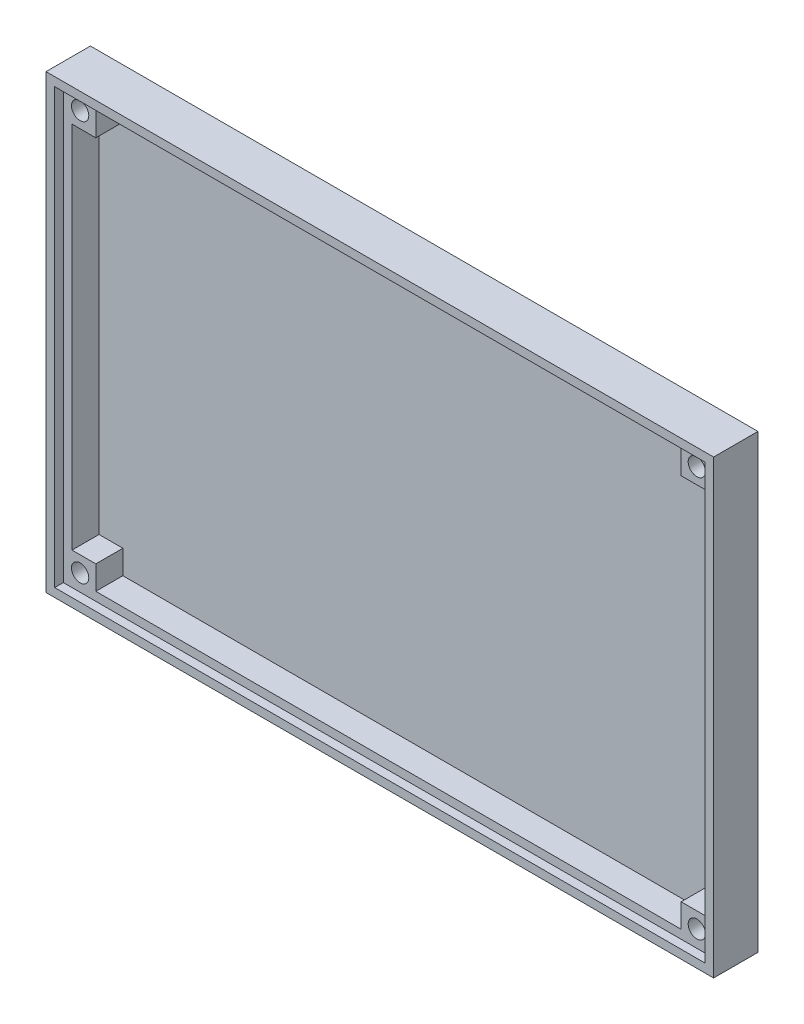
SolidWorks part; units mm, degrees
ref_plane "Front Plane" through (0, 0, 0) normal (0, 0, 1) x (1, 0, 0)
ref_plane "Top Plane" through (0, 0, 0) normal (0, 1, 0) x (1, 0, 0)
ref_plane "Right Plane" through (0, 0, 0) normal (1, 0, 0) x (0, 0, -1)
sketch "Sketch1" plane through (0, 0, 0) normal (0, 0, 1) x (1, 0, 0)
  line L1 (-60.1, 40.1) -> (60.1, 40.1)
  line L2 (-60.1, 40.1) -> (-60.1, -40.1)
  line L3 (-60.1, -40.1) -> (60.1, -40.1)
  line L4 (60.1, 40.1) -> (60.1, -40.1)
  line L5 (-60.1, 40.1) -> (60.1, -40.1) construction
  line L6 (-60.1, -40.1) -> (60.1, 40.1) construction
  point P0 (0, 0)
  dimension "D1" = 80.2
  dimension "D2" = 120.2
extrude "Boss-Extrude1" add sketch "Sketch1" along normal blind 1.6
sketch "Sketch2" plane through (0, 0, 0) normal (0, 0, 1) x (1, 0, 0)
  line L0 (-60.1, 40.1) -> (-60.1, -40.1)
  line L1 (-60.1, -40.1) -> (60.1, -40.1)
  line L2 (60.1, -40.1) -> (60.1, 40.1)
  line L3 (60.1, 40.1) -> (-60.1, 40.1)
  line L4 (-61.7, 41.7) -> (-61.7, -41.7)
  line L5 (-61.7, -41.7) -> (61.7, -41.7)
  line L6 (61.7, -41.7) -> (61.7, 41.7)
  line L7 (61.7, 41.7) -> (-61.7, 41.7)
  dimension "D1" = 1.6
  dimension "D2" = 1.6
  dimension "D3" = 1.6
  dimension "D4" = 1.6
extrude "Boss-Extrude2" add sketch "Sketch2" along normal blind 8.2
sketch "Sketch3" plane through (0, 0, 1.6) normal (0, 0, 1) x (1, 0, 0)
  line L0 (60.1, -40.1) -> (60.1, 40.1) construction
  line L3 (-58.5, 34.1) -> (-54.1, 34.1)
  line L4 (-54.1, 38.5) -> (-54.1, 34.1)
  line L6 (60.1, 40.1) -> (60.1, -40.1)
  line L7 (58.5, 34.1) -> (54.1, 34.1)
  line L8 (54.1, 38.5) -> (54.1, 34.1)
  line L9 (60.1, -40.1) -> (60.1, 40.1) construction
  line L10 (60.1, 40.1) -> (-60.1, 40.1)
  line L11 (60.1, -40.1) -> (-60.1, -40.1)
  line L13 (58.5, -34.1) -> (54.1, -34.1)
  line L14 (54.1, -38.5) -> (54.1, -34.1)
  line L16 (-60.1, -40.1) -> (-60.1, 40.1)
  line L17 (-58.5, -34.1) -> (-54.1, -34.1)
  line L18 (-54.1, -38.5) -> (-54.1, -34.1)
  line L19 (54.1, 38.5) -> (-54.1, 38.5)
  line L20 (58.5, 34.1) -> (58.5, -34.1)
  line L21 (54.1, -38.5) -> (-54.1, -38.5)
  line L22 (-58.5, -34.1) -> (-58.5, 34.1)
  line L23 (-60.1, -40.1) -> (60.1, -40.1) construction
  line L24 (-60.1, 40.1) -> (-60.1, -40.1) construction
  line L25 (60.1, 40.1) -> (-60.1, 40.1) construction
  line L26 (60.1, 40.1) -> (-60.1, 40.1) construction
  dimension "D1" = 6
  dimension "D2" = 6
  dimension "D3" = 6
  dimension "D4" = 6
  dimension "D6" = 1.6
  dimension "D7" = 1.6
  dimension "D8" = 1.6
extrude "Boss-Extrude3" add sketch "Sketch3" along normal blind 5
sketch "Sketch4" plane through (0, 0, 6.6) normal (0, 0, 1) x (1, 0, 0)
  circle A0 centre (-57, 37) radius 1.6
  circle A1 centre (57, 37) radius 1.6
  circle A2 centre (57, -37) radius 1.6
  circle A3 centre (-57, -37) radius 1.6
  point P9 (0, 0)
  point P10 (0, 0)
  point P11 (0, 0)
  point P12 (0, 0)
  point P13 (0, 0)
  point P14 (0, 0)
  dimension "D3" = 3.2
  dimension "D1" = 57
  dimension "D2" = 37
  dimension "D4" = 74
  dimension "D5" = 114
extrude "Cut-Extrude1" cut sketch "Sketch4" against normal blind 5
